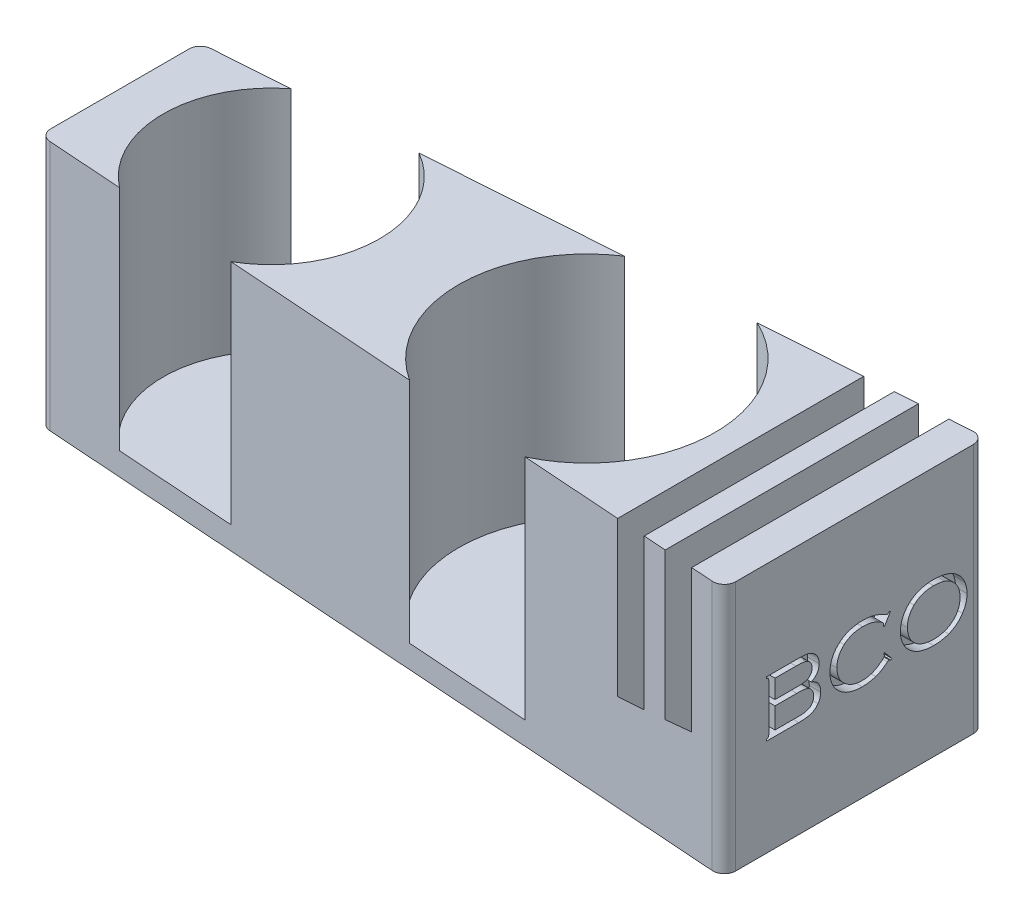
SolidWorks part; units mm, degrees
ref_plane "Front Plane" through (0, 0, 0) normal (0, 0, 1) x (1, 0, 0)
ref_plane "Top Plane" through (0, 0, 0) normal (0, 1, 0) x (1, 0, 0)
ref_plane "Right Plane" through (0, 0, 0) normal (1, 0, 0) x (0, 0, -1)
sketch "Sketch1" plane through (0, 0, 0) normal (0, 1, 0) x (1, 0, 0)
  line L0 (0, 7) -> (64.5, 11.5)
  line L1 (0, 7) -> (0, -7)
  line L2 (64.5, 11.5) -> (64.5, -11.5)
  line L3 (0, -7) -> (64.5, -11.5)
  line L4 (0, 7) -> (64.5, -11.5) construction
  line L5 (64.5, 11.5) -> (0, -7) construction
extrude "Boss-Extrude1" add sketch "Sketch1" along normal blind 2
sketch "Sketch2" plane through (0, 2, 0) normal (0, 1, 0) x (1, 0, 0)
  line L0 (61.5023, 11.2909) -> (61.4974, -11.2905)
  line L1 (64.5, 11.5) -> (0, 7) construction
  line L2 (0, -7) -> (64.5, -11.5) construction
  line L3 (61.4974, -11.2905) -> (64.5, -11.5)
  line L4 (64.5, -11.5) -> (64.5, 11.5)
  line L5 (64.5, 11.5) -> (61.5023, 11.2909)
extrude "Boss-Extrude2" add sketch "Sketch2" along normal blind 20 contours L0 L3 L4 L5
sketch "Sketch4" plane through (0, 2, 0) normal (0, 1, 0) x (1, 0, 0)
  line L0 (61.4974, -11.2905) -> (61.5023, 11.2909)
  line L1 (0, -7) -> (61.4974, -11.2905) construction
  line L2 (61.5023, 11.2909) -> (0, 7) construction
  line L3 (61.5023, 11.2909) -> (58.9952, 11.1159)
  line L4 (58.9952, 11.1159) -> (58.9952, -11.1159)
  line L5 (58.9952, -11.1159) -> (61.4974, -11.2905)
extrude "Boss-Extrude3" add sketch "Sketch4" along normal blind 20
sketch "Sketch5" plane through (58.9952, 0, 0) normal (-1, 0, 0) x (0, 0, 1)
  circle A0 centre (0, 14.2529) radius 12.25
extrude "Cut-Extrude1" cut sketch "Sketch5" against normal blind 2.5
sketch "Sketch6" plane through (61.4952, 0, 0) normal (-1, 0, 0) x (0, 0, 1)
  line L1 (-11.2904, 9.5) -> (11.2904, 9.5)
  line L2 (-11.2904, 9.5) -> (-11.2904, 22)
  line L3 (-11.2904, 22) -> (11.2904, 22)
  line L4 (11.2904, 9.5) -> (11.2904, 22)
  line L5 (11.2904, 9.5) -> (11.2904, 19.0058) construction
extrude "Cut-Extrude3" cut sketch "Sketch6" along normal blind 2.5
sketch "Sketch8" plane through (0, 2, 0) normal (0, 1, 0) x (1, 0, 0)
  line L0 (58.9952, 11.1159) -> (57.0066, 10.9772)
  line L1 (58.9952, 11.1159) -> (0, 7) construction
  line L2 (57.0066, 10.9772) -> (57.0066, -10.9772)
  line L3 (0, -7) -> (58.9952, -11.1159) construction
  line L4 (57.0066, -10.9772) -> (58.9952, -11.1159)
  line L5 (58.9952, -11.1159) -> (58.9952, 11.1159)
extrude "Boss-Extrude4" add sketch "Sketch8" along normal blind 20
sketch "Sketch9" plane through (0, 2, 0) normal (0, 1, 0) x (1, 0, 0)
  line L0 (57.0066, 10.9772) -> (54.5089, 10.8029)
  line L1 (57.0066, 10.9772) -> (0, 7) construction
  line L2 (54.5089, 10.8029) -> (54.5089, -10.8029)
  line L3 (0, -7) -> (57.0066, -10.9772) construction
  line L4 (54.5089, -10.8029) -> (57.0066, -10.9772)
  line L5 (57.0066, -10.9772) -> (57.0066, 10.9772)
extrude "Boss-Extrude5" add sketch "Sketch9" along normal blind 20
sketch "Sketch10" plane through (54.5089, 0, 0.0001) normal (-1, 0, 0) x (0, 0, 1)
  circle A0 centre (0, 14.224) radius 12.25
extrude "Cut-Extrude4" cut sketch "Sketch10" against normal blind 2.5
sketch "Sketch11" plane through (57.0089, 0, 0.0001) normal (-1, 0, 0) x (0, 0, 1)
  line L0 (-10.9774, 8.7872) -> (-10.9774, 22)
  line L1 (-10.9774, 22) -> (11.0716, 22)
  line L2 (11.0716, 22) -> (10.9773, 8.787)
  line L3 (10.9773, 8.787) -> (-10.9774, 8.7872)
  line L4 (10.8029, 22) -> (11.1159, 22) construction
extrude "Cut-Extrude5" cut sketch "Sketch11" along normal blind 2.5
sketch "Sketch12" plane through (0, 2, 0) normal (0, 1, 0) x (1, 0, 0)
  line L0 (54.5089, 10.8029) -> (0, 7)
  line L1 (0, 7) -> (0, -7)
  line L2 (0, -7) -> (54.5089, -10.8029)
  line L3 (54.5089, -10.8029) -> (54.5089, 10.8029)
  line L5 (54.5089, 10.8029) -> (0, 7) construction
extrude "Boss-Extrude6" add sketch "Sketch12" along normal blind 20
sketch "Sketch13" plane through (0, 22, 0) normal (0, 1, 0) x (1, 0, 0)
  circle A0 centre (13.3, 0) radius 9.5
extrude "Cut-Extrude6" cut sketch "Sketch13" against normal blind 20
sketch "Sketch14" plane through (0, 22, 0) normal (0, 1, 0) x (1, 0, 0)
  circle A0 centre (41, 0) radius 11.25
extrude "Cut-Extrude7" cut sketch "Sketch14" against normal blind 20
sketch "Sketch15" plane through (64.5, 0, 0) normal (1, 0, 0) x (0, 0, -1)
  text T0 "BCO" font "Copperplate Gothic Light" height in points 24
extrude "Cut-Extrude8" cut sketch "Sketch15" against normal blind 1
fillet "Fillet2" radius 1 4 edges at (0, 11, -7) (0, 11, 7) (64.5, 11, -11.5) (64.5, 11, 11.5)
